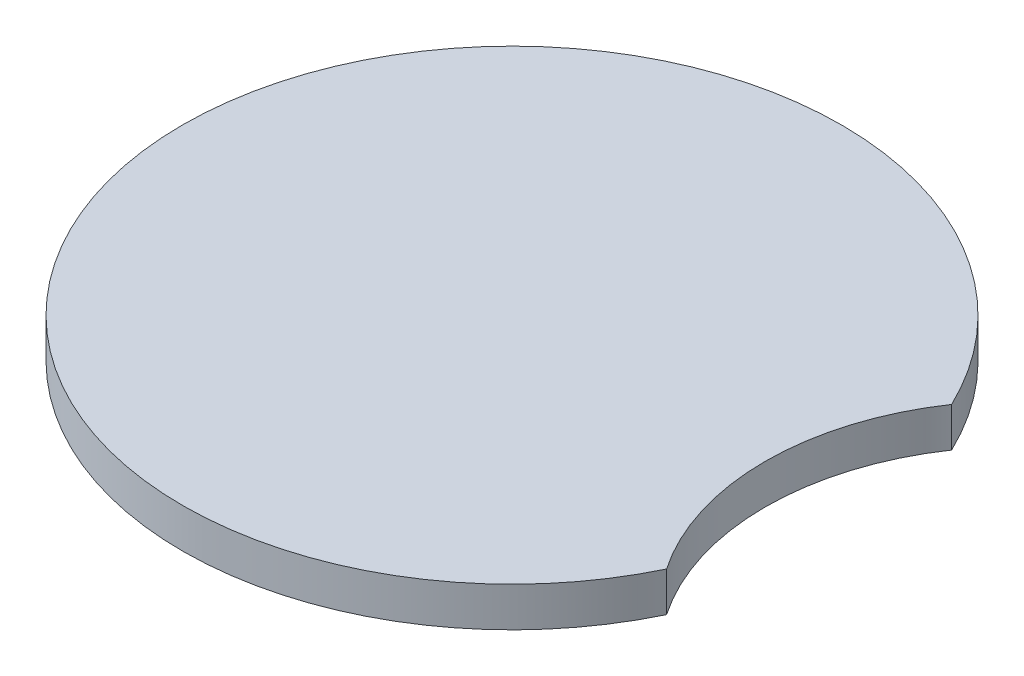
SolidWorks part; units mm, degrees
ref_plane "Alzado" through (0, 0, 0) normal (0, 0, 1) x (1, 0, 0)
ref_plane "Planta" through (0, 0, 0) normal (0, 1, 0) x (1, 0, 0)
ref_plane "Vista lateral" through (0, 0, 0) normal (1, 0, 0) x (0, 0, -1)
sketch "Croquis1" plane through (0, 0, 0) normal (0, 1, 0) x (1, 0, 0)
  arc A0 (22.5402, 10.8139) -> (22.5402, -10.8139) centre (0, 0) ccw
  arc A1 (22.5402, 10.8139) -> (22.5402, -10.8139) centre (38.4132, 0) ccw
  dimension "D1" = 50
extrude "Saliente-Extruir1" add sketch "Croquis1" along normal blind 3
